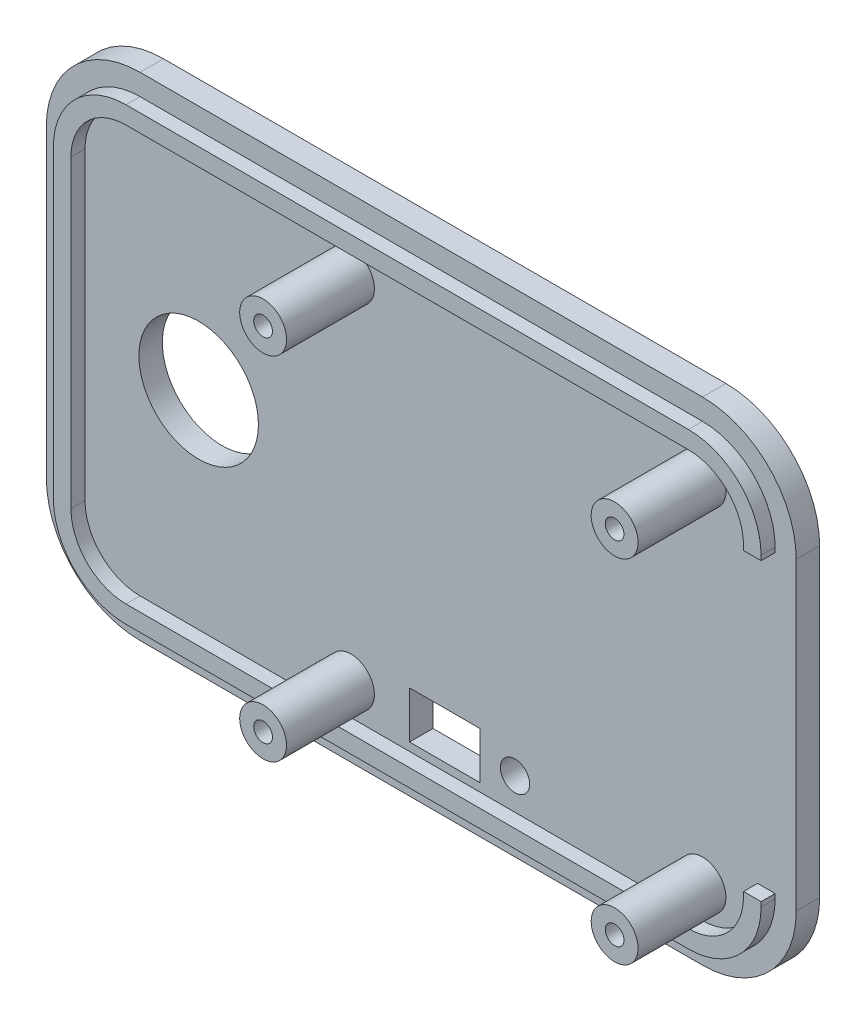
SolidWorks part; units mm, degrees
ref_plane "Front Plane" through (0, 0, 0) normal (0, 0, 1) x (1, 0, 0)
ref_plane "Top Plane" through (0, 0, 0) normal (0, 1, 0) x (1, 0, 0)
ref_plane "Right Plane" through (0, 0, 0) normal (1, 0, 0) x (0, 0, -1)
sketch "Sketch1" plane through (0, 0, 0) normal (0, 0, 1) x (1, 0, 0)
  line L1 (-32, 21) -> (32, 21)
  line L2 (-32, 21) -> (-32, -21)
  line L3 (-32, -21) -> (32, -21)
  line L4 (32, 21) -> (32, -21)
  point P4 (0, 21)
  point P6 (32, 0)
  dimension "D1" = 64
  dimension "D2" = 42
extrude "Boss-Extrude1" add sketch "Sketch1" along normal blind 2
fillet "Fillet1" radius 8 4 edges at (-32, -21, 1) (32, -21, 1) (-32, 21, 1) (32, 21, 1)
sketch "Sketch2" plane through (0, 0, 2) normal (0, 0, 1) x (1, 0, 0)
  line L1 (-24, 19.2) -> (24, 19.2)
  line L2 (-30.2, 13) -> (-30.2, -13)
  line L3 (-24, -19.2) -> (24, -19.2)
  line L4 (30.2, 13) -> (30.2, -13)
  line L5 (-24, 17.7) -> (24, 17.7)
  line L6 (-28.7, 13) -> (-28.7, -13)
  line L7 (-24, -17.7) -> (24, -17.7)
  line L8 (28.7, 13) -> (28.7, -13)
  arc A0 (24, -19.2) -> (30.2, -13) centre (24, -13) ccw
  arc A1 (-30.2, -13) -> (-24, -19.2) centre (-24, -13) ccw
  arc A2 (-24, 19.2) -> (-30.2, 13) centre (-24, 13) ccw
  arc A3 (24, 19.2) -> (30.2, 13) centre (24, 13) cw
  arc A4 (24, -17.7) -> (28.7, -13) centre (24, -13) ccw
  arc A5 (-28.7, -13) -> (-24, -17.7) centre (-24, -13) ccw
  arc A6 (-24, 17.7) -> (-28.7, 13) centre (-24, 13) ccw
  arc A7 (24, 17.7) -> (28.7, 13) centre (24, 13) cw
  point P4 (0, 19.2)
  point P6 (-30.2, 0)
  point P9 (30.2, -19.2)
  point P14 (-30.2, 19.2)
  point P17 (30.2, 19.2)
  point P22 (0, 17.7)
  point P23 (28.7, 0)
  point P26 (28.7, -17.7)
  point P31 (-28.7, 17.7)
  point P34 (28.7, 17.7)
  dimension "D3" = 6.2
  dimension "D6" = 4.7
  dimension "D1" = 60.4
  dimension "D2" = 38.4
  dimension "D4" = 57.4
  dimension "D5" = 35.4
extrude "Boss-Extrude2" add sketch "Sketch2" along normal blind 1.2
sketch "Sketch3" plane through (0, 0, 2) normal (0, 0, -1) x (-1, 0, 0)
  line L1 (-27, 12.6) -> (-33, 12.6)
  line L2 (-27, 12.6) -> (-27, -12.6)
  line L3 (-27, -12.6) -> (-33, -12.6)
  line L4 (-33, 12.6) -> (-33, -12.6)
  point P4 (-30, 12.6)
  point P6 (-27, 0)
  dimension "D1" = 6
  dimension "D2" = 25.2
  dimension "D3" = 30
extrude "Cut-Extrude1" cut sketch "Sketch3" against normal blind 1.2
sketch "Sketch4" plane through (0, 0, 2) normal (0, 0, 1) x (1, 0, 0)
  line L0 (1.76, 0) -> (-1.76, 0) construction
  circle A0 centre (-6, 15) radius 2
  circle A1 centre (24, 15) radius 2
  circle A2 centre (24, -15) radius 2
  circle A3 centre (-6, -15) radius 2
  point P4 (0, 0)
  dimension "D1" = 4
  dimension "D4" = 24
  dimension "D2" = 6
  dimension "D3" = 15
extrude "Boss-Extrude3" add sketch "Sketch4" along normal blind 7.5
sketch "Sketch5" plane through (0, 0, 9.5) normal (0, 0, 1) x (1, 0, 0)
  circle A0 centre (24, 15) radius 0.8
  circle A1 centre (24, 15) radius 2 construction
  point P4 (-6, 15)
  point P5 (-6, -15)
  point P6 (24, -15)
  dimension "D1" = 1.6
extrude "Cut-Extrude2" cut sketch "Sketch5" against normal blind 5
pattern_sketch "Sketch-Pattern1" of "Cut-Extrude2" driven by "Sketch5"
sketch "Sketch6" plane through (0, 0, 2) normal (0, 0, 1) x (1, 0, 0)
  line L1 (-1, -13) -> (5, -13)
  line L2 (-1, -13) -> (-1, -17)
  line L3 (-1, -17) -> (5, -17)
  line L4 (5, -13) -> (5, -17)
  circle A0 centre (-19, 0) radius 5.1
  circle A1 centre (8, -15) radius 1.25
  point P4 (2, -13)
  point P10 (5, -15)
  dimension "D1" = 10.2
  dimension "D2" = 2.5
  dimension "D3" = 19
  dimension "D4" = 8
  dimension "D5" = 15
  dimension "D6" = 6
  dimension "D7" = 4
  dimension "D8" = 2
  dimension "D9" = 15
extrude "Cut-Extrude3" cut sketch "Sketch6" against normal through all
